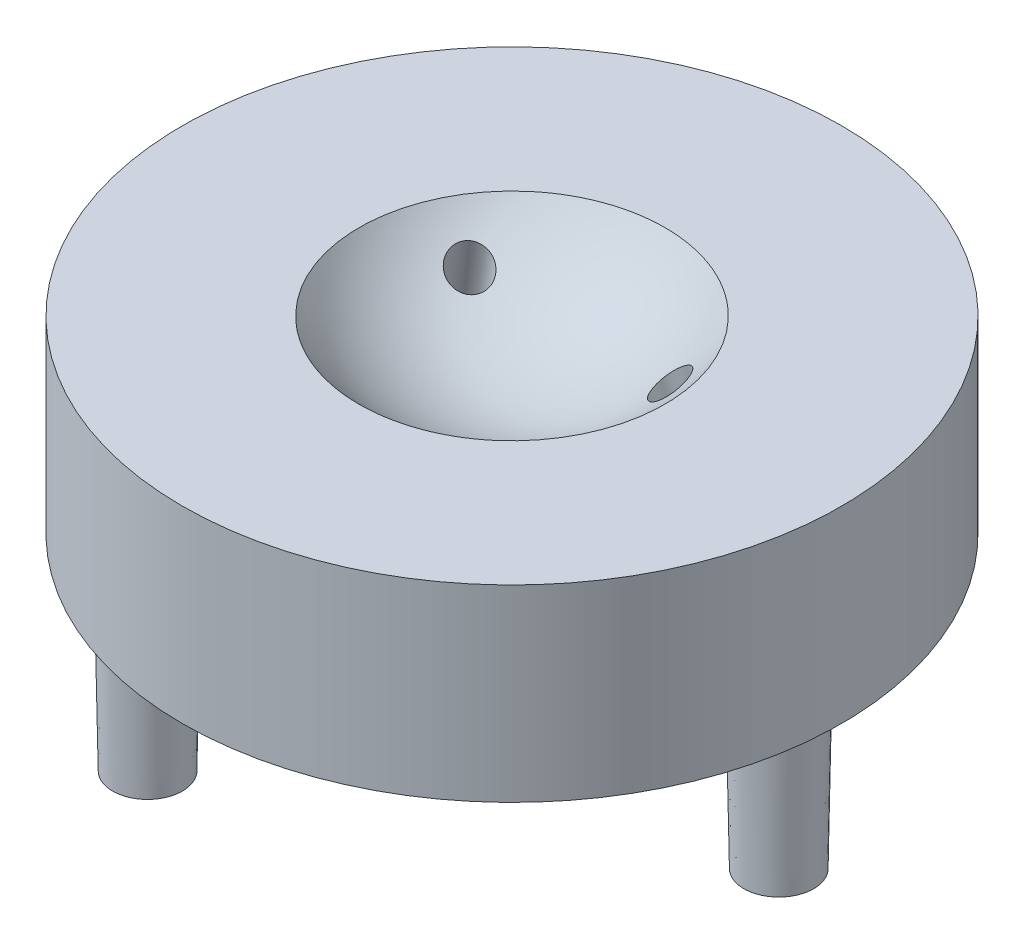
SolidWorks part; units mm, degrees
ref_plane "前视基准面" through (0, 0, 0) normal (0, 0, 1) x (1, 0, 0)
ref_plane "上视基准面" through (0, 0, 0) normal (0, 1, 0) x (1, 0, 0)
ref_plane "右视基准面" through (0, 0, 0) normal (1, 0, 0) x (0, 0, -1)
other "Configuration Table"
sketch "草图1" plane through (0, 0, 0) normal (0, 1, 0) x (1, 0, 0)
  line L1 (-28.1, 43.1) -> (28.1, 43.1)
  line L2 (-43.1, 28.1) -> (-43.1, -28.1)
  line L3 (-28.1, -43.1) -> (28.1, -43.1)
  line L4 (43.1, 28.1) -> (43.1, -28.1)
  line L5 (-43.1, 43.1) -> (43.1, -43.1) construction
  line L6 (-43.1, -43.1) -> (43.1, 43.1) construction
  arc A0 (-43.1, -28.1) -> (-28.1, -43.1) centre (-28.1, -28.1) ccw
  arc A1 (28.1, -43.1) -> (43.1, -28.1) centre (28.1, -28.1) ccw
  arc A2 (28.1, 43.1) -> (43.1, 28.1) centre (28.1, 28.1) cw
  arc A3 (-28.1, 43.1) -> (-43.1, 28.1) centre (-28.1, 28.1) ccw
  point P0 (0, 0)
  dimension "D3" = 15
  dimension "D1" = 86.2
  dimension "D2" = 86.2
extrude "凸台-拉伸1" add sketch "草图1" along normal blind 6
sketch "草图6" plane through (0, 6, 0) normal (0, 1, 0) x (1, 0, 0)
  circle A0 centre (0, 0) radius 10.5
extrude "切除-拉伸2" cut sketch "草图6" against normal blind 10 flip side to cut
sketch "草图7" plane through (0, 0, 0) normal (0, -1, 0) x (1, 0, 0)
  circle A0 centre (8.5, 0) radius 1.2
  circle A1 centre (-4.25, -7.3612) radius 1.2
  circle A2 centre (-4.25, 7.3612) radius 1.2
  point P9 (0, 0)
  dimension "D1" = 2.4
  dimension "D2" = 8.5
  dimension "D3" = 3
extrude "凸台-拉伸3" add sketch "草图7" along normal blind 5 draft 1
ref_plane "基准面1" through (0, 9.5, 0) normal (0, 1, 0) x (1, 0, 0)
sketch "草图8" plane through (0, 9.5, 0) normal (0, 1, 0) x (1, 0, 0)
  line L0 (0, 6) -> (0, -6)
  arc A0 (0, 6) -> (0, -6) centre (0, 0) ccw
  dimension "D1" = 6
revolve "切除-旋转1" cut sketch "草图8" angle 360 about L0
sketch "草图10" plane through (0, 0, 0) normal (0, -1, 0) x (1, 0, 0)
  circle A0 centre (0, 0) radius 6
extrude "切除-拉伸3" cut sketch "草图10" against normal blind 3 draft 71
sketch "草图12" plane through (0, 0, 0) normal (1, 0, 0) x (0, 0, -1)
  line L0 (-3.1772, 6.4267) -> (-5.6528, -1.384)
sweep "切除-扫描1" cut path "草图12" circular profile diameter 1.2 parameters "D3"=1.2
pattern_circular "阵列(圆周)1" count 3 over 360 about axis through (0, 6, 0) along (0, 1, 0) of "切除-扫描1"
